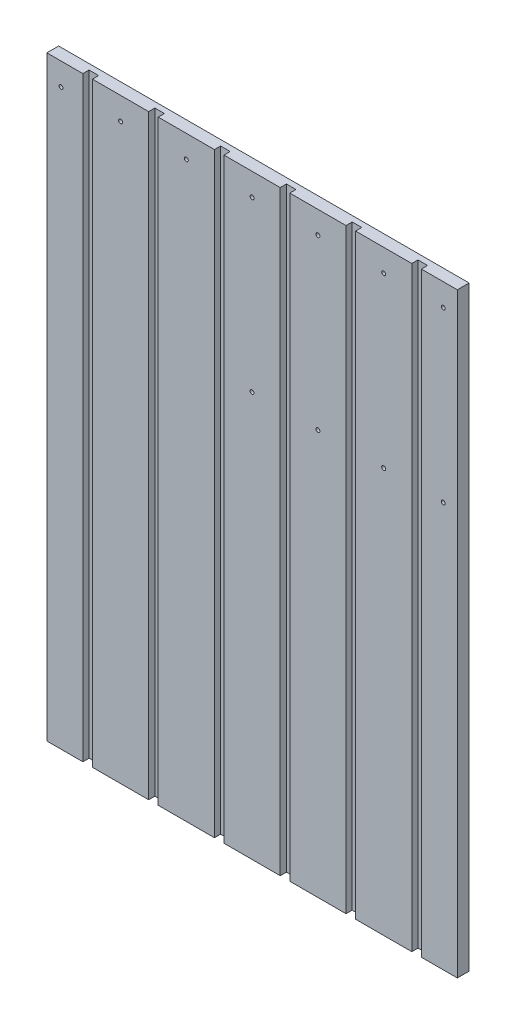
SolidWorks part; units mm, degrees
material "Buche"
ref_plane "Ebene vorne" through (0, 0, 0) normal (0, 0, 1) x (1, 0, 0)
ref_plane "Ebene oben" through (0, 0, 0) normal (0, 1, 0) x (1, 0, 0)
ref_plane "Ebene rechts" through (0, 0, 0) normal (1, 0, 0) x (0, 0, -1)
sketch "Skizze1" plane through (0, 0, 0) normal (0, 0, 1) x (1, 0, 0)
  line L1 (365, 530) -> (-365, 530)
  line L2 (365, 530) -> (365, -530)
  line L3 (365, -530) -> (-365, -530)
  line L4 (-365, 530) -> (-365, -530)
  line L5 (365, 530) -> (-365, -530) construction
  line L6 (365, -530) -> (-365, 530) construction
  point P0 (0, 0)
  dimension "D1" = 730
  dimension "D2" = 1060
extrude "Aufsatz-Linear austragen1" add sketch "Skizze1" along normal blind 21
sketch "Skizze2" plane through (0, 0, 21) normal (0, 0, 1) x (1, 0, 0)
  line L0 (0, 0) -> (0, 572.5339) construction
  line L1 (365, 530) -> (-365, 530) construction
  line L2 (50, 530) -> (67, 530)
  line L3 (50, 530) -> (50, -530)
  line L4 (50, -530) -> (67, -530)
  line L5 (67, 530) -> (67, -530)
  line L6 (-365, -530) -> (365, -530) construction
  line L8 (167, 530) -> (184, 530)
  line L9 (167, 530) -> (167, -530)
  line L10 (167, -530) -> (184, -530)
  line L11 (184, 530) -> (184, -530)
  line L12 (284, 530) -> (301, 530)
  line L13 (284, 530) -> (284, -530)
  line L14 (284, -530) -> (301, -530)
  line L15 (301, 530) -> (301, -530)
  line L23 (-284, 530) -> (-301, 530)
  line L24 (-301, 530) -> (-301, -530)
  line L25 (-284, -530) -> (-301, -530)
  line L26 (-284, 530) -> (-284, -530)
  line L27 (-167, 530) -> (-184, 530)
  line L28 (-184, 530) -> (-184, -530)
  line L29 (-167, -530) -> (-184, -530)
  line L30 (-167, 530) -> (-167, -530)
  line L31 (-50, 530) -> (-67, 530)
  line L32 (-67, 530) -> (-67, -530)
  line L33 (-50, -530) -> (-67, -530)
  line L34 (-50, 530) -> (-50, -530)
  dimension "D1" = 17
  dimension "D2" = 50
  dimension "D3" = 100
  dimension "D4" = 100
extrude "Schnitt-Linear austragen1" cut sketch "Skizze2" against normal blind 11
sketch "Skizze3" plane through (0, 0, 21) normal (0, 0, 1) x (1, 0, 0)
  line L0 (0, 0) -> (484.7536, 0) construction
  line L1 (0, 0) -> (0, 553.0018) construction
  line L2 (67, 490) -> (167, 490) construction
  line L3 (0, 190) -> (422.2459, 190) construction
  line L4 (67, -530) -> (67, 530) construction
  line L5 (167, 530) -> (167, -530) construction
  line L6 (184, 490) -> (284, 490) construction
  line L7 (184, -530) -> (184, 530) construction
  line L8 (284, 530) -> (284, -530) construction
  line L9 (301, 490) -> (365, 490) construction
  line L10 (301, -530) -> (301, 530) construction
  line L11 (365, -530) -> (365, 530) construction
  line L12 (117, 490) -> (117, 190) construction
  line L13 (234, 490) -> (234, 190) construction
  line L14 (340, 490) -> (340, 190) construction
  line L15 (365, 530) -> (301, 530) construction
  line L16 (284, 530) -> (184, 530) construction
  circle A0 centre (0, 490) radius 3.5
  circle A1 centre (117, 490) radius 3.5
  circle A2 centre (234, 490) radius 3.5
  circle A3 centre (340, 490) radius 3.5
  circle A4 centre (340, 190) radius 3.5
  circle A5 centre (234, 190) radius 3.5
  circle A6 centre (117, 190) radius 3.5
  circle A7 centre (0, 190) radius 3.5
  circle A8 centre (-340, 490) radius 3.5
  circle A9 centre (-234, 490) radius 3.5
  circle A10 centre (-117, 490) radius 3.5
  dimension "D1" = 7
  dimension "D2" = 340
  dimension "D3" = 40
  dimension "D4" = 340
extrude "Schnitt-Linear austragen2" cut sketch "Skizze3" against normal blind 40
